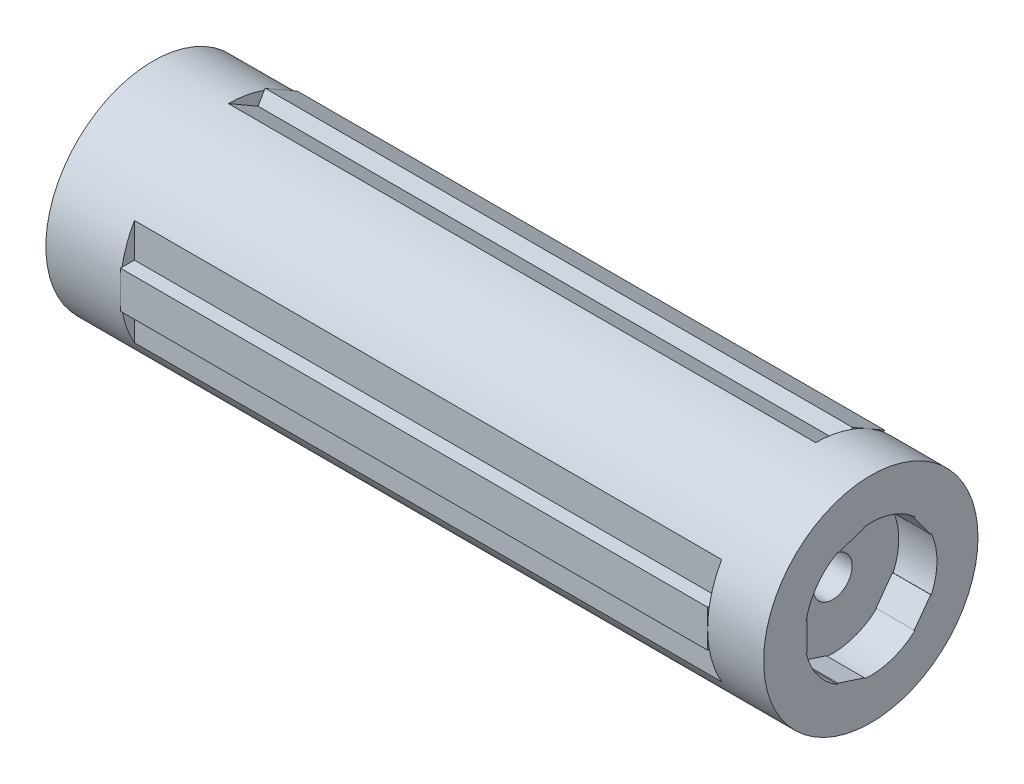
SolidWorks part; units mm, degrees
material "PVC hart"
ref_plane "Ebene vorne" through (0, 0, 0) normal (0, 0, 1) x (1, 0, 0)
ref_plane "Ebene oben" through (0, 0, 0) normal (0, 1, 0) x (1, 0, 0)
ref_plane "Ebene rechts" through (0, 0, 0) normal (1, 0, 0) x (0, 0, -1)
sketch "Skizze1" plane through (0, 0, 0) normal (1, 0, 0) x (0, 0, -1)
  circle A0 centre (0, 0) radius 11.5
  dimension "D1" = 23
extrude "Aufsatz-Linear austragen1" add sketch "Skizze1" along normal blind 77
sketch "Skizze2" plane through (77, 0, 0) normal (1, 0, 0) x (0, 0, -1)
  line L0 (-15.3822, 0) -> (15.9559, 0) construction
  line L1 (-6.9427, 1.4864) -> (-6.8427, 1.4864)
  line L2 (-6.8427, 1.4864) -> (-6.8427, -1.5136)
  line L3 (-6.8427, -1.5136) -> (-6.9368, -1.5136)
  line L4 (-0.7318, 7.0622) -> (-0.7009, 6.9671)
  line L5 (-0.7009, 6.9671) -> (-3.554, 6.04)
  line L6 (-3.554, 6.04) -> (-3.5831, 6.1295)
  line L7 (6.4904, 2.8783) -> (6.4095, 2.8195)
  line L8 (6.4095, 2.8195) -> (4.6462, 5.2466)
  line L9 (4.6462, 5.2466) -> (4.7223, 5.3019)
  line L10 (4.7431, -5.2833) -> (4.6622, -5.2245)
  line L11 (4.6622, -5.2245) -> (6.4255, -2.7975)
  line L12 (6.4255, -2.7975) -> (6.5017, -2.8528)
  line L13 (-3.559, -6.1436) -> (-3.5281, -6.0484)
  line L14 (-3.5281, -6.0484) -> (-0.675, -6.9755)
  line L15 (-0.675, -6.9755) -> (-0.7041, -7.065)
  arc A0 (-6.9368, -1.5136) -> (-3.559, -6.1436) centre (0, 0) ccw
  arc A1 (-3.5831, 6.1295) -> (-6.9427, 1.4864) centre (0, 0) ccw
  arc A2 (4.7223, 5.3019) -> (-0.7318, 7.0622) centre (0, 0) ccw
  arc A3 (6.5017, -2.8528) -> (6.4904, 2.8783) centre (0, 0) ccw
  arc A4 (-0.7041, -7.065) -> (4.7431, -5.2833) centre (0, 0) ccw
  point P28 (0, 0)
  dimension "D1" = 14.2
  dimension "D2" = 3
  dimension "D3" = 0.1
  dimension "D4" = 5
extrude "Schnitt-Linear austragen1" cut sketch "Skizze2" against normal blind 4.1
sketch "Skizze3" plane through (72.9, 0, 0) normal (1, 0, 0) x (0, 0, -1)
  circle A0 centre (0, 0) radius 2.1
  dimension "D1" = 4.2
extrude "Schnitt-Linear austragen2" cut sketch "Skizze3" against normal blind 3
sketch "Skizze4" plane through (0, 0, 0) normal (-1, 0, 0) x (0, 0, 1)
  circle A0 centre (0, 0) radius 9.6
  dimension "D1" = 19.2
extrude "Schnitt-Linear austragen3" cut sketch "Skizze4" against normal blind 12.75
sketch "Skizze7" plane through (77, 0, 0) normal (1, 0, 0) x (0, 0, -1)
  line L0 (0, 13.4409) -> (0, -14.2481) construction
  line L1 (-11.5, 7.5) -> (-10, 7.5)
  line L2 (-11.5, 7.5) -> (-11.5, -7.5)
  line L3 (-11.5, -7.5) -> (-10, -7.5)
  line L4 (-10, 7.5) -> (-10, -7.5)
  dimension "D1" = 1.5
  dimension "D2" = 15
  dimension "D3" = 10
extrude "Schnitt-Linear austragen4" cut sketch "Skizze7" against normal blind 63 from offset 6 offset against normal yes
sketch "Skizze8" plane through (0, 0, 10) normal (0, 0, 1) x (1, 0, 0)
  line L0 (71, -5.6789) -> (71, 5.6789) construction
  line L1 (8, 2) -> (71, 2)
  line L2 (8, 2) -> (8, -2)
  line L3 (8, -2) -> (71, -2)
  line L4 (71, 2) -> (71, -2)
  line L5 (8, 2) -> (71, -2) construction
  line L6 (8, -2) -> (71, 2) construction
  line L7 (12.65, 0) -> (-12.65, 0) construction
  point P0 (39.5, 0)
  dimension "D1" = 31.5
  dimension "D3" = 63
  dimension "D4" = 4
extrude "Aufsatz-Linear austragen2" add sketch "Skizze8" along normal blind 1.5
sketch "Skizze10" plane through (12.75, 0, 0) normal (-1, 0, 0) x (0, 0, 1)
  line L1 (4.0389, -2.2407) -> (3.96, 2.3774)
  line L2 (3.96, 2.3774) -> (-0.0789, 4.6181)
  line L3 (-0.0789, 4.6181) -> (-4.0389, 2.2407)
  line L4 (-4.0389, 2.2407) -> (-3.96, -2.3774)
  line L5 (-3.96, -2.3774) -> (0.0789, -4.6181)
  line L6 (0.0789, -4.6181) -> (4.0389, -2.2407)
  circle A0 centre (0, 0) radius 4 construction
  dimension "D1" = 8
extrude "Schnitt-Linear austragen6" cut sketch "Skizze10" against normal blind 13.5
sketch "Skizze12" plane through (26.25, 0, 0) normal (-1, 0, 0) x (0, 0, 1)
  circle A0 centre (0, 0) radius 3
  dimension "D1" = 6
extrude "Schnitt-Linear austragen7" cut sketch "Skizze12" against normal blind 2
pattern_circular "Kreismuster3" count 3 over 360 about axis through (0, 0, 0) along (1, 0, 0) of "Aufsatz-Linear austragen2", "Schnitt-Linear austragen4"
sketch "Skizze13" plane through (69.9, 0, 0) normal (1, 0, 0) x (0, 0, -1)
  circle A0 centre (0, 0) radius 8.5
extrude "Schnitt-Linear austragen8" cut sketch "Skizze13" against normal blind 40
